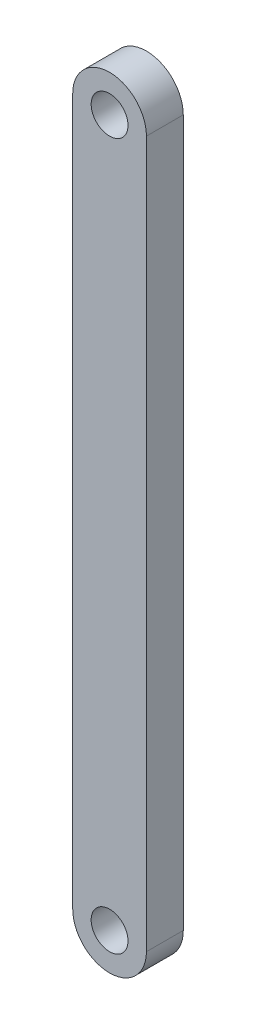
SolidWorks part; units mm, degrees
ref_plane "Alzado" through (0, 0, 0) normal (0, 0, 1) x (1, 0, 0)
ref_plane "Planta" through (0, 0, 0) normal (0, 1, 0) x (1, 0, 0)
ref_plane "Vista lateral" through (0, 0, 0) normal (1, 0, 0) x (0, 0, -1)
sketch "Croquis1" plane through (0, 0, 0) normal (0, 0, 1) x (1, 0, 0)
  line L0 (0, 0) -> (0, 115) construction
  line L1 (-6, 0) -> (-6, 115)
  line L2 (6, 0) -> (6, 115)
  arc A0 (-6, 0) -> (6, 0) centre (0, 0) ccw
  circle A1 centre (0, 0) radius 3
  arc A2 (6, 115) -> (-6, 115) centre (0, 115) ccw
  circle A3 centre (0, 115) radius 3
  dimension "D1" = 12
  dimension "D2" = 6
  dimension "D4" = 6
  dimension "D3" = 115
extrude "Saliente-Extruir1" add sketch "Croquis1" along normal blind 6
